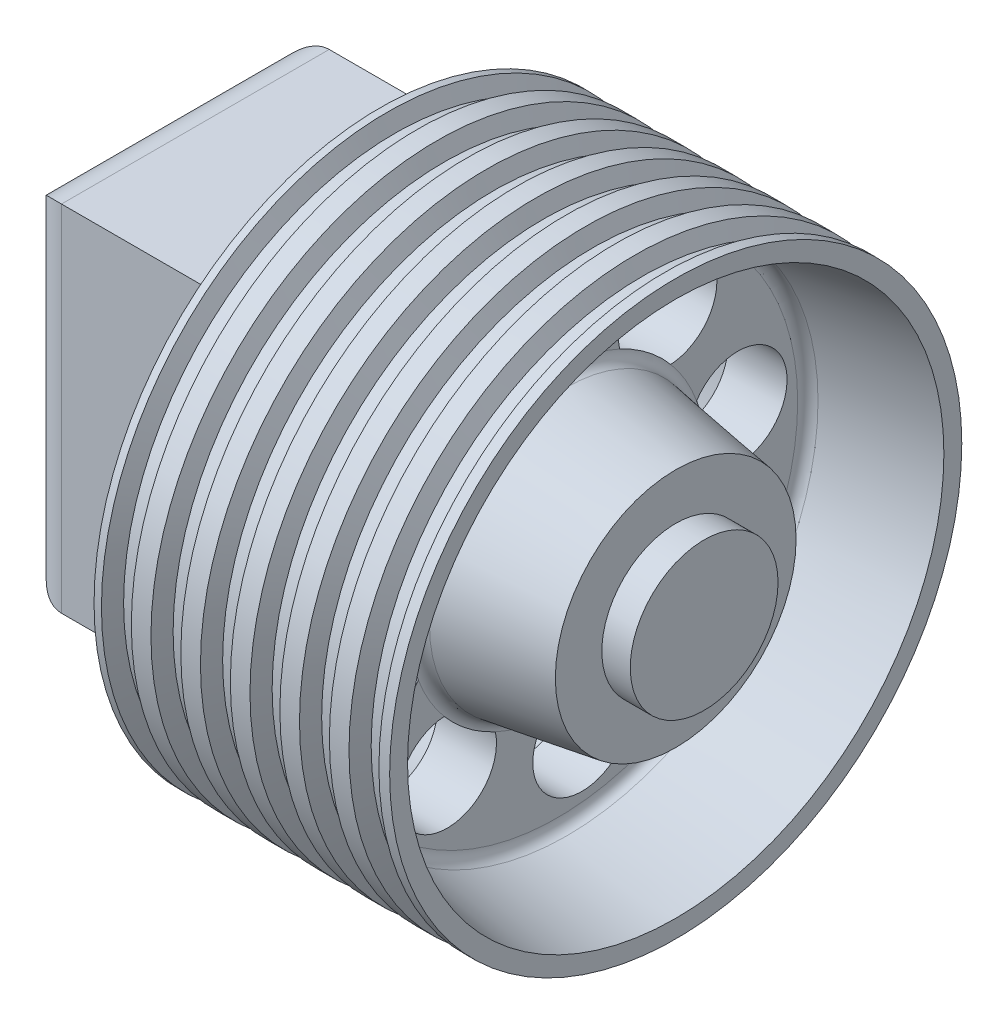
SolidWorks part; units mm, degrees
ref_plane "前视基准面" through (0, 0, 0) normal (0, 0, 1) x (1, 0, 0)
ref_plane "上视基准面" through (0, 0, 0) normal (0, 1, 0) x (1, 0, 0)
ref_plane "右视基准面" through (0, 0, 0) normal (1, 0, 0) x (0, 0, -1)
sketch "草图2" plane through (0, 0, 0) normal (0, 0, 1) x (1, 0, 0)
  line L1 (-11.8028, 4.7714) -> (-11.8028, 4.5292)
  line L2 (-11.8028, 4.5292) -> (-13.4028, 4.2792)
  line L3 (-13.4028, 4.2792) -> (-13.4028, 2.7792)
  line L4 (-13.4028, 2.7792) -> (-11.8028, 2.5292)
  line L5 (-11.8028, 2.5292) -> (-11.8028, 1.7714)
  line L8 (-11.8028, 4.7714) -> (-15.8028, 4.7714)
  line L9 (-11.8028, 1.7714) -> (-15.8028, 1.7714)
  line L10 (-13.8028, 6.6869) -> (-13.8028, -0.4398) construction
  line L11 (-18.6499, 0.9003) -> (-11.4183, 0.9003) construction
  line L12 (-15.8028, 2.5292) -> (-15.8028, 1.7714)
  line L13 (-14.2028, 2.7792) -> (-15.8028, 2.5292)
  line L14 (-14.2028, 4.2792) -> (-14.2028, 2.7792)
  line L15 (-15.8028, 4.5292) -> (-14.2028, 4.2792)
  line L16 (-15.8028, 4.7714) -> (-15.8028, 4.5292)
  line L17 (-15.8028, -2.9708) -> (-15.8028, -2.7286)
  line L18 (-15.8028, -2.7286) -> (-14.2028, -2.4786)
  line L19 (-14.2028, -2.4786) -> (-14.2028, -0.9786)
  line L20 (-14.2028, -0.9786) -> (-15.8028, -0.7286)
  line L21 (-15.8028, -0.7286) -> (-15.8028, 0.0292)
  line L22 (-11.8028, 0.0292) -> (-15.8028, 0.0292)
  line L23 (-11.8028, -2.9708) -> (-15.8028, -2.9708)
  line L24 (-11.8028, -0.7286) -> (-11.8028, 0.0292)
  line L25 (-13.4028, -0.9786) -> (-11.8028, -0.7286)
  line L26 (-13.4028, -2.4786) -> (-13.4028, -0.9786)
  line L27 (-11.8028, -2.7286) -> (-13.4028, -2.4786)
  line L28 (-11.8028, -2.9708) -> (-11.8028, -2.7286)
  point P18 (-13.8028, 1.7714)
  point P19 (-13.8028, 4.7714)
  point P30 (-13.8028, -2.9708)
  point P31 (-13.8028, 0.0292)
  dimension "D2" = 3
revolve "旋转1" add sketch "草图2" angle 360 about L11
sketch "草图3" plane through (0, 0, 0) normal (0, 0, 1) x (1, 0, 0)
  line L2 (-15.7028, 4.7714) -> (-15.6028, 4.5714)
  line L4 (-11.8028, 4.7714) -> (-15.8028, 4.7714) construction
  line L5 (-15.6028, 4.5714) -> (-15.3983, 4.5714)
  line L6 (-15.3983, 4.5714) -> (-15.2983, 4.7714)
  line L7 (-15.2983, 4.7714) -> (-15.7028, 4.7714)
  line L8 (-14.9328, 4.5714) -> (-14.7283, 4.5714)
  line L9 (-14.6283, 4.7714) -> (-15.0328, 4.7714)
  line L10 (-14.7283, 4.5714) -> (-14.6283, 4.7714)
  line L11 (-15.0328, 4.7714) -> (-14.9328, 4.5714)
  line L12 (-14.2628, 4.5714) -> (-14.0583, 4.5714)
  line L13 (-13.9583, 4.7714) -> (-14.3628, 4.7714)
  line L14 (-14.0583, 4.5714) -> (-13.9583, 4.7714)
  line L15 (-14.3628, 4.7714) -> (-14.2628, 4.5714)
  line L16 (-13.5928, 4.5714) -> (-13.3883, 4.5714)
  line L17 (-13.2883, 4.7714) -> (-13.6928, 4.7714)
  line L18 (-13.3883, 4.5714) -> (-13.2883, 4.7714)
  line L19 (-13.6928, 4.7714) -> (-13.5928, 4.5714)
  line L20 (-12.9228, 4.5714) -> (-12.7183, 4.5714)
  line L21 (-12.6183, 4.7714) -> (-13.0228, 4.7714)
  line L22 (-12.7183, 4.5714) -> (-12.6183, 4.7714)
  line L23 (-13.0228, 4.7714) -> (-12.9228, 4.5714)
  line L24 (-12.2528, 4.5714) -> (-12.0483, 4.5714)
  line L25 (-11.9483, 4.7714) -> (-12.3528, 4.7714)
  line L26 (-12.0483, 4.5714) -> (-11.9483, 4.7714)
  line L27 (-12.3528, 4.7714) -> (-12.2528, 4.5714)
  dimension "D1" = 6
revolve "切除-旋转3" cut sketch "草图3" angle 360 about L11
fillet "圆角3" radius 0.15 1 edges at (-13.4028, 0.9003, 3.3789)
fillet "圆角4" radius 0.15 1 edges at (-13.4028, 0.9003, 1.8789)
sketch "草图7" plane through (-13.4028, 0, 0) normal (1, 0, 0) x (0, 0, -1)
  circle A1 centre (2.441, 1.2319) radius 0.6656
extrude "切除-拉伸1" cut sketch "草图7" against normal blind 10
pattern_circular "阵列(圆周)1" count 8 every 45 about axis through (0, 0.9003, 0) along (1, 0, 0) of "切除-拉伸1"
sketch "草图9" plane through (-15.8028, 0, 0) normal (-1, 0, 0) x (0, 0, 1)
  line L5 (-1.8114, 3.2983) -> (1.8114, 3.2983)
  line L6 (-1.8114, 3.2983) -> (-1.8114, -1.4977)
  line L7 (-1.8114, -1.4977) -> (1.8114, -1.4977)
  line L8 (1.8114, 3.2983) -> (1.8114, -1.4977)
  line L9 (-1.8114, 3.2983) -> (1.8114, -1.4977) construction
  line L10 (-1.8114, -1.4977) -> (1.8114, 3.2983) construction
  point P0 (0, 0.9003)
extrude "凸台-拉伸1" add sketch "草图9" along normal blind 3
fillet "圆角6" radius 0.5 4 edges at (-18.8028, -1.4977, 0) (-18.8028, 0.9003, -1.8114) (-18.8028, 3.2983, 0) (-18.8028, 0.9003, 1.8114)
sketch "草图10" plane through (-11.8028, 0, 0) normal (1, 0, 0) x (0, 0, -1)
  circle A0 centre (0, 0.9003) radius 1
extrude "凸台-拉伸2" add sketch "草图10" against normal up to surface and the other way up to vertex
sketch "草图11" plane through (0, 0, -1.8114) normal (0, 0, -1) x (-1, 0, 0)
  line L0 (18.3028, -1.4977) -> (18.3028, 3.2983) construction
  line L1 (18.3171, -0.0566) -> (17.1915, -0.0566)
  line L2 (19.4142, -0.076) -> (19.4142, -0.0566)
  line L3 (18.3104, 1.8572) -> (17.1915, 1.8572)
  line L4 (17.1915, -0.0566) -> (17.1915, 1.8572)
  line L5 (18.3104, 1.8572) -> (18.3171, -0.0566)
  point P0 (18.3028, 0.9003)
  line M6 (18.3028, -1.4977) -> (18.3028, 3.2983)
extrude "凸台-拉伸3" add sketch "草图11" along normal blind 1 contours L4 L1 L3 M6
